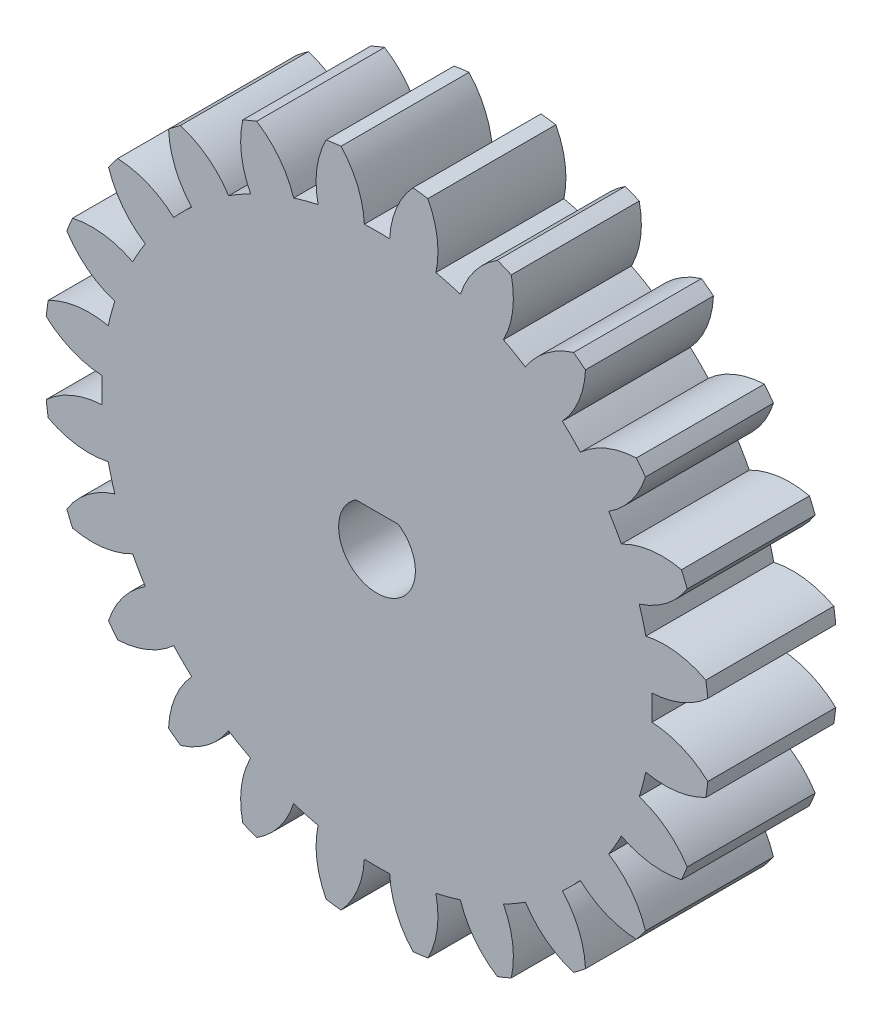
SolidWorks part; units mm, degrees
ref_plane "Front Plane" through (0, 0, 0) normal (0, 0, 1) x (1, 0, 0)
ref_plane "Top Plane" through (0, 0, 0) normal (0, 1, 0) x (1, 0, 0)
ref_plane "Right Plane" through (0, 0, 0) normal (1, 0, 0) x (0, 0, -1)
sketch "Sketch6" plane through (0, 0, 0) normal (0, 0, 1) x (1, 0, 0)
  circle A0 centre (0, 0) radius 21.5
  circle A1 centre (0, 0) radius 24
  circle A2 centre (0, 0) radius 26
  dimension "D1" = 43
  dimension "D2" = 48
  dimension "D3" = 52
extrude "Boss-Extrude1" add sketch "Sketch6" along normal blind 10 contours A2
sketch "Sketch7" plane through (0, 0, 10) normal (0, 0, 1) x (1, 0, 0)
  line L0 (0, -26) -> (0, 26) construction
  line L1 (-0.9902, 21.4772) -> (0, 0) construction
  line L2 (0.9902, 21.4772) -> (0, 0) construction
  line L3 (-1.5697, 23.9486) -> (1.5697, 23.9486) construction
  line L4 (-2.4225, 25.8869) -> (-0.4898, 21.4944) construction
  line L5 (-1.5697, 23.9486) -> (0, 24.6393) construction
  line L6 (-1.5697, 23.9486) -> (3.194, 24.2608) construction
  line L7 (0, 0) -> (3.3937, 25.7776) construction
  line L8 (1.5697, 23.9486) -> (4.6822, 23.5388) construction
  circle A0 centre (0, 0) radius 26 construction
  arc A1 (-0.9902, 21.4772) -> (-2.811, 25.8476) centre (-7.9117, 21.1581) ccw
  circle A2 centre (0, 0) radius 21.5 construction
  circle A3 centre (0, 0) radius 26 construction
  arc A4 (0.9902, 21.4772) -> (2.811, 25.8476) centre (7.9117, 21.1581) cw
  circle A5 centre (0, 0) radius 24 construction
  arc A6 (2.811, 25.8476) -> (-2.811, 25.8476) centre (0, 0) ccw
  arc A7 (0.9902, 21.4772) -> (-0.9902, 21.4772) centre (0, 0) ccw
  point P16 (-1.5697, 23.9486)
  point P20 (1.5697, 23.9486)
  dimension "D1" = 20
  dimension "D2" = 7.5
extrude "Cut-Extrude3" cut sketch "Sketch7" against normal through all
pattern_circular "CirPattern2" count 24 over 360 about axis through (0, 0, 0) along (0, 0, 1) of "Cut-Extrude3"
sketch "Sketch8" plane through (0, 0, 10) normal (0, 0, 1) x (1, 0, 0)
  line L0 (-1.6583, 2.5) -> (1.6583, 2.5)
  arc A0 (-1.6583, 2.5) -> (1.6583, 2.5) centre (0, 0) ccw
  point P1 (0, -3)
  dimension "D1" = 6
  dimension "D2" = 5.5
extrude "Cut-Extrude4" cut sketch "Sketch8" against normal through all
sketch "Sketch9" plane through (0, 0, 0) normal (0, 0, -1) x (-1, 0, 0)
  line L0 (-1.6583, 2.5) -> (1.6583, 2.5) construction
  line L1 (-1.6583, 2.5) -> (1.6583, 2.5)
  circle A0 centre (0, 0) radius 5
  arc A2 (-1.6583, 2.5) -> (1.6583, 2.5) centre (0, 0) ccw construction
  arc A3 (-1.6583, 2.5) -> (1.6583, 2.5) centre (0, 0) ccw
  dimension "D1" = 10
extrude "Boss-Extrude2" add sketch "Sketch9" along normal blind 4
equation "\"module\"= 2"
equation "\"number of teeth\"= 24"
equation "\"pressure angle\"= 20"
equation "\"add\"= \"module\""
equation "\"ded\"= \"module\" * 1.25"
equation "\"pitch d\"= \"number of teeth\" * \"module\""
equation "\"outside d\"= \"pitch d\" + 2 * \"add\""
equation "\"root d\"= \"pitch d\" - 2 * \"ded\""
equation "\"D2@Sketch6\"=\"pitch d\""
equation "\"D1@Sketch6\"=\"root d\""
equation "\"D3@Sketch6\"=\"outside d\""
equation "\"D1@Sketch7\"=\"pressure angle\""
equation "\"D2@Sketch7\"=180/\"number of teeth\""
